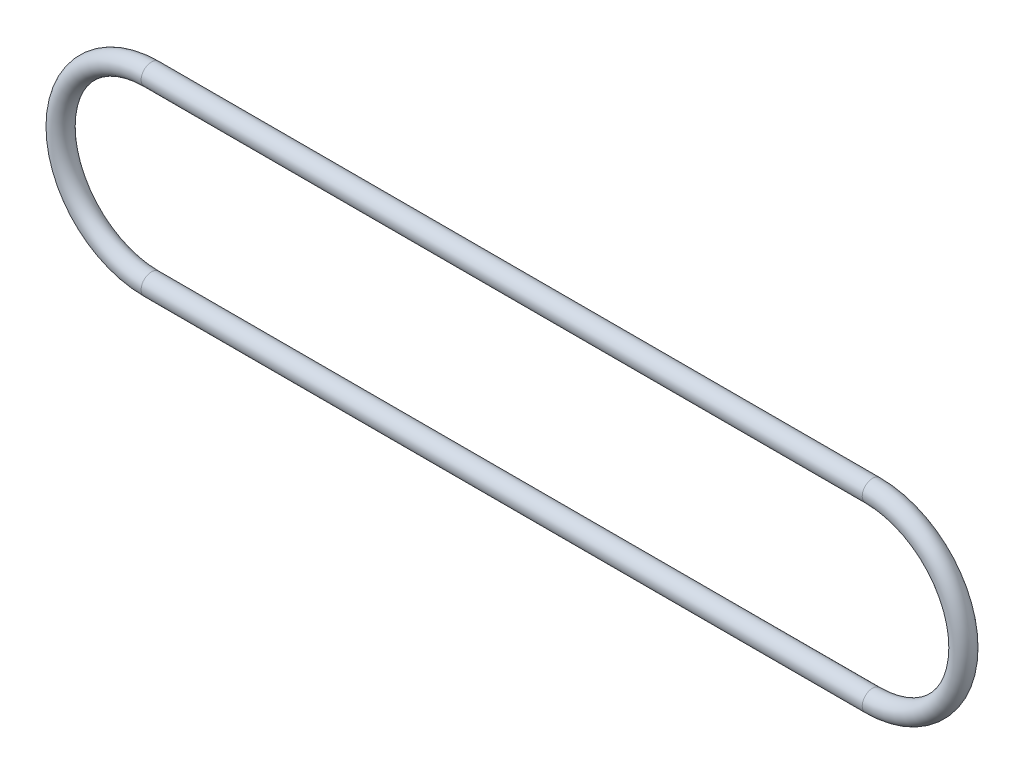
SolidWorks part; units mm, degrees
material "EPDM 60 Durometer"
ref_plane "Front Plane" through (0, 0, 0) normal (0, 0, 1) x (1, 0, 0)
ref_plane "Top Plane" through (0, 0, 0) normal (0, 1, 0) x (1, 0, 0)
ref_plane "Right Plane" through (0, 0, 0) normal (1, 0, 0) x (0, 0, -1)
sketch "Sketch1" plane through (0, 0, 0) normal (0, 0, 1) x (1, 0, 0)
  line L1 (-246.4969, 271.5598) -> (626.5031, 271.5598)
  line L3 (-246.4969, 51.5598) -> (626.5031, 51.5598)
  arc A0 (-246.4969, 51.5598) -> (-246.4969, 271.5598) centre (-246.4969, 161.5598) cw
  arc A1 (626.5031, 271.5598) -> (626.5031, 51.5598) centre (626.5031, 161.5598) cw
  point P6 (-356.4969, 161.5598)
  point P7 (736.5031, 161.5598)
  dimension "D1" = 1093
  dimension "D2" = 220
sweep "Sweep2" add path "Sketch1" circular profile diameter 25 parameters "D3"=25
